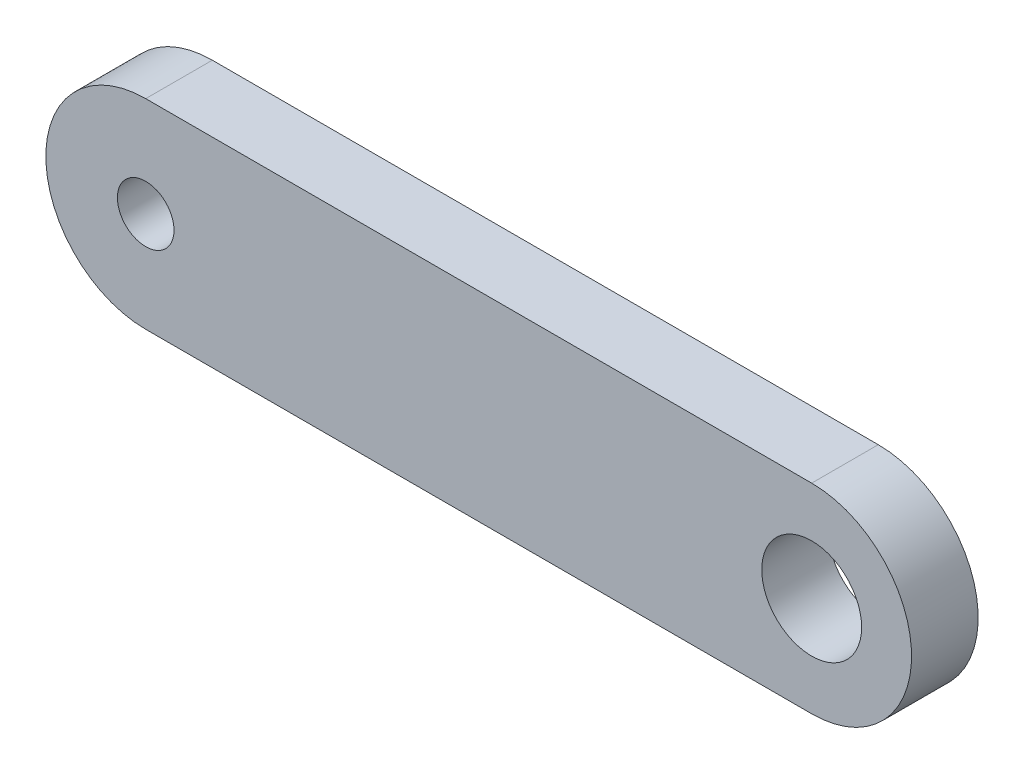
SolidWorks part; units mm, degrees
ref_plane "前视基准面" through (0, 0, 0) normal (0, 0, 1) x (1, 0, 0)
ref_plane "上视基准面" through (0, 0, 0) normal (0, 1, 0) x (1, 0, 0)
ref_plane "右视基准面" through (0, 0, 0) normal (1, 0, 0) x (0, 0, -1)
other "Configuration Table"
sketch "草图1" plane through (0, 0, 0) normal (0, 0, 1) x (1, 0, 0)
  line L0 (0, 0) -> (20, 0) construction
  line L1 (0, 3) -> (20, 3)
  line L2 (0, -3) -> (20, -3)
  arc A0 (0, 3) -> (0, -3) centre (0, 0) ccw
  arc A1 (20, -3) -> (20, 3) centre (20, 0) ccw
  circle A2 centre (0, 0) radius 1.5
  circle A3 centre (20, 0) radius 1.5
  point P3 (10, 0)
  dimension "D2" = 3
  dimension "D3" = 3
  dimension "D4" = 3
  dimension "D1" = 20
extrude "凸台-拉伸1" add sketch "草图1" along normal blind 2
sketch "草图4" plane through (0, 0, 0) normal (0, 0, -1) x (-1, 0, 0)
  circle A0 centre (0, 0) radius 1.5 construction
  circle A1 centre (0, 0) radius 1.5
  circle A2 centre (0, 0) radius 0.85
  circle M5 centre (0, 0) radius 1.5
  dimension "D1" = 1.7
extrude "凸台-拉伸6" add sketch "草图4" against normal through all contours A2 M5 | A1
sketch "草图6" plane through (0, 0, 2) normal (0, 0, 1) x (1, 0, 0)
  point P0 (20, 0)
